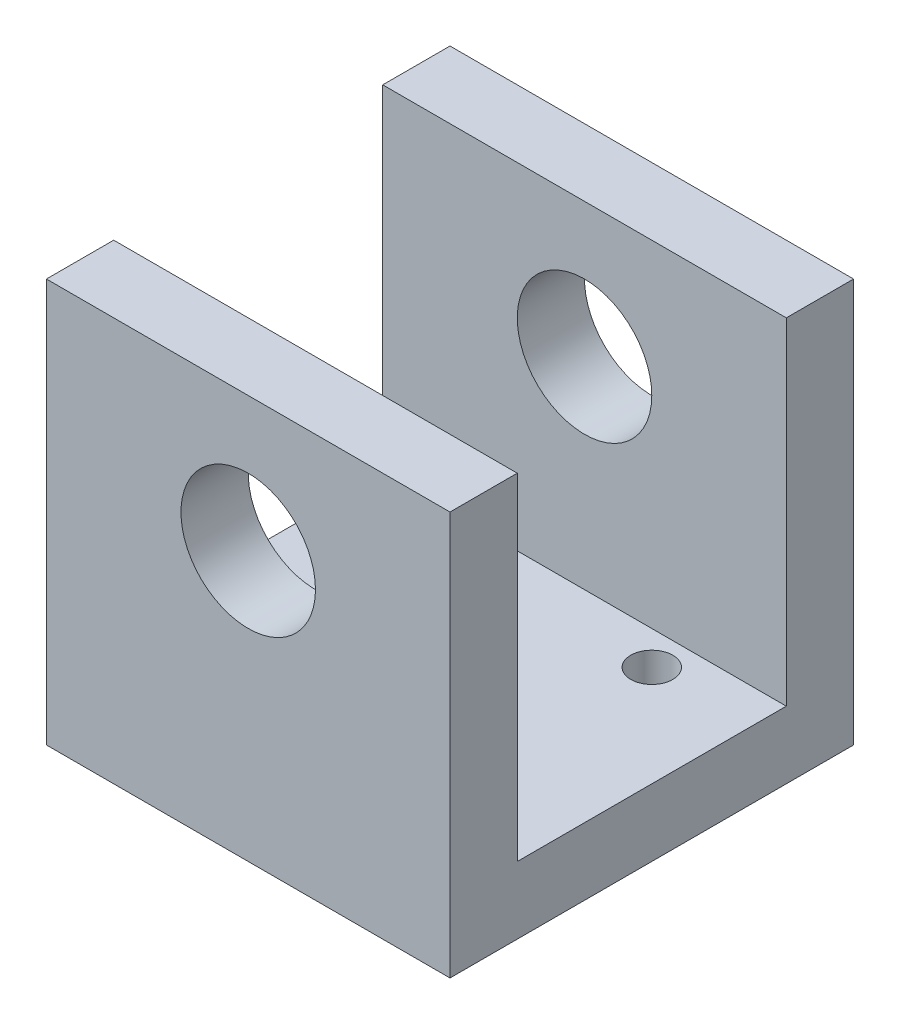
SolidWorks part; units mm, degrees
material "6061-T6 (SS)"
ref_plane "Front" through (0, 0, 0) normal (0, 0, 1) x (1, 0, 0)
ref_plane "Top" through (0, 0, 0) normal (0, 1, 0) x (1, 0, 0)
ref_plane "Right" through (0, 0, 0) normal (1, 0, 0) x (0, 0, -1)
sketch "Sketch1" plane through (0, 0, 0) normal (1, 0, 0) x (0, 0, -1)
  line L0 (0, 0) -> (76.2, 0)
  line L1 (76.2, 0) -> (76.2, 76.2)
  line L2 (76.2, 76.2) -> (63.5, 76.2)
  line L3 (63.5, 76.2) -> (63.5, 12.7)
  line L4 (63.5, 12.7) -> (12.7, 12.7)
  line L5 (12.7, 12.7) -> (12.7, 76.2)
  line L6 (12.7, 76.2) -> (0, 76.2)
  line L7 (0, 76.2) -> (0, 0)
  dimension "D1" = 76.2
  dimension "D2" = 12.7
  dimension "D3" = 12.7
  dimension "D4" = 12.7
  dimension "D5" = 76.2
  dimension "D6" = 76.2
extrude "Boss-Extrude1" add sketch "Sketch1" along normal blind 76.2
sketch "Sketch2" plane through (0, 0, 0) normal (0, 0, 1) x (1, 0, 0)
  line L0 (0, 76.2) -> (0, 0) construction
  line L1 (76.2, 0) -> (0, 0) construction
  circle A0 centre (38.1, 50.8) radius 12.7
  dimension "D1" = 25.4
  dimension "D2" = 38.1
  dimension "D3" = 50.8
extrude "Cut-Extrude1" cut sketch "Sketch2" against normal through all
hole_wizard "5/16 (0.3125) Diameter Hole1" positions "Sketch3" profile "Sketch4" hole size "5/16" standard "ANSI Inch"
sketch "Sketch3" plane through (0, 12.7, 0) normal (0, 1, 0) x (1, 0, 0)
  line L0 (0, 63.5) -> (0, 12.7) construction
  line L1 (76.2, 0) -> (0, 0) construction
  point P0 (19.05, 19.05)
  dimension "D1" = 19.05
  dimension "D2" = 19.05
sketch "Sketch4" plane through (19.05, 12.7, -19.05) normal (1, 0, 0) x (0, 0, 1)
  line L0 (0, 0) -> (0, 12.7)
  line L1 (0, 12.7) -> (3.9687, 12.7)
  line L2 (3.9687, 12.7) -> (3.9687, 0)
  line L5 (3.9687, 0) -> (0, 0)
  line L11 (0, -6.35) -> (0, 107.95) construction
  dimension "Thru Hole Dia." = 7.9375
  dimension "Thru Hole Depth" = 12.7
pattern_linear "LPattern1" count 2 spacing 38.1 along (1, 0, 0) count 2 spacing 38.1 along (0, 0, -1) of "5/16 (0.3125) Diameter Hole1"
